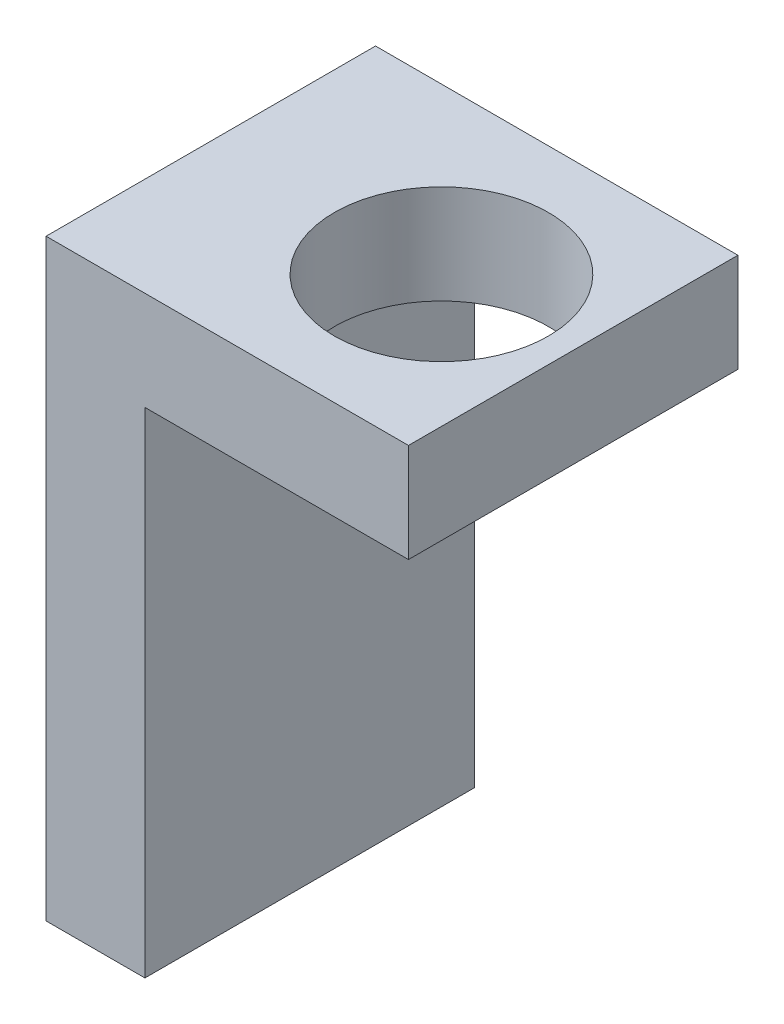
SolidWorks part; units mm, degrees
ref_plane "Front Plane" through (0, 0, 0) normal (0, 0, 1) x (1, 0, 0)
ref_plane "Top Plane" through (0, 0, 0) normal (0, 1, 0) x (1, 0, 0)
ref_plane "Right Plane" through (0, 0, 0) normal (1, 0, 0) x (0, 0, -1)
sketch "Sketch1" plane through (0, 0, 0) normal (0, 1, 0) x (1, 0, 0)
  line L0 (-2.5, 5) -> (-2.5, -5)
  line L1 (-2.5, 5) -> (5.5, 5)
  line L2 (-5.5, 5) -> (-5.5, -5) construction
  line L3 (-2.5, -5) -> (5.5, -5)
  line L4 (5.5, 5) -> (5.5, -5)
  line L5 (-2.5, 0) -> (1.5, 0) construction
  circle A0 centre (1.5, 0) radius 1.5
  point P0 (0, 0)
  dimension "D5" = 3
  dimension "D1" = 11
  dimension "D2" = 10
  dimension "D3" = 3
  dimension "D4" = 4
extrude "Boss-Extrude1" add sketch "Sketch1" against normal blind 3
sketch "Sketch2" plane through (0, 0, 0) normal (0, 1, 0) x (1, 0, 0)
  line L0 (-2.5, 5) -> (-5.5, 5)
  line L1 (-5.5, 5) -> (-5.5, -5)
  line L2 (-5.5, -5) -> (-2.5, -5)
  line L3 (-2.5, -5) -> (-2.5, 5)
extrude "Boss-Extrude2" add sketch "Sketch2" against normal blind 18
sketch "Sketch3" plane through (0, 0, 0) normal (0, 1, 0) x (1, 0, 0)
  circle A0 centre (1.5, 0) radius 3.25
  dimension "D1" = 6.5
extrude "Cut-Extrude1" cut sketch "Sketch3" against normal blind 3.2
